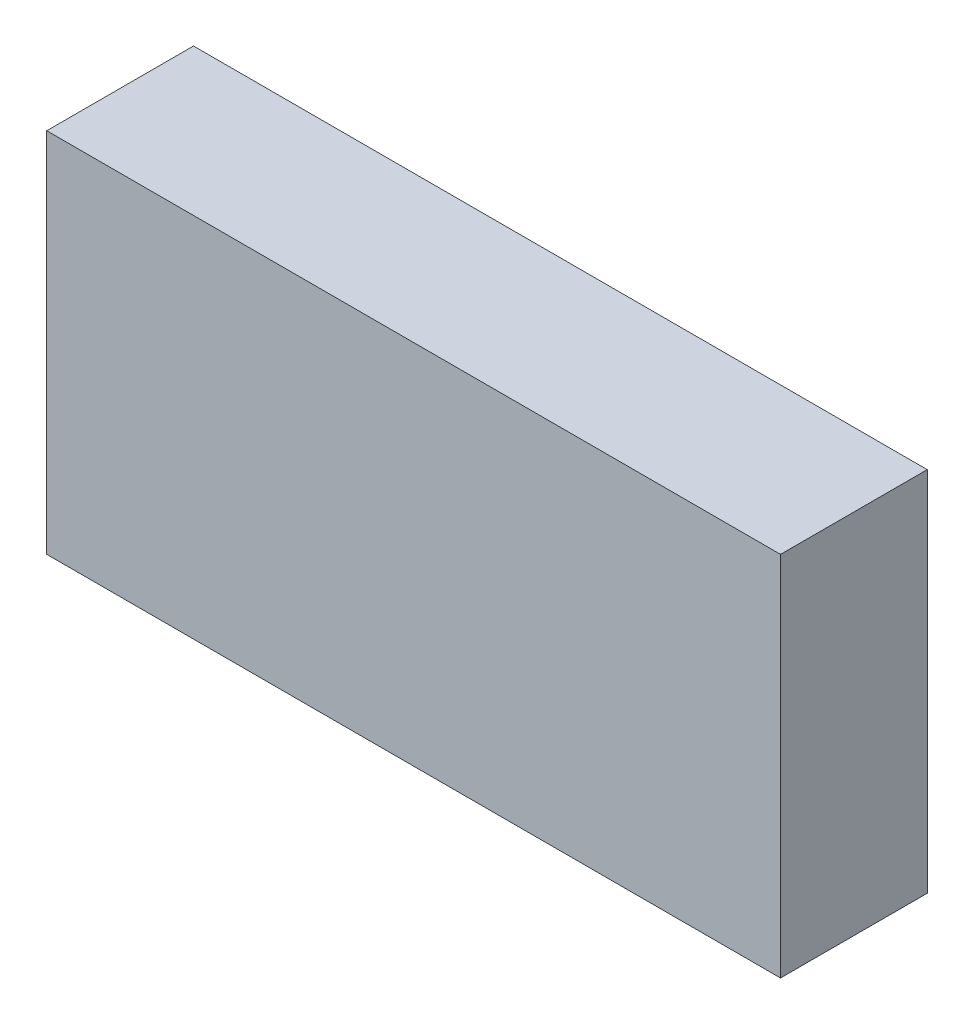
SolidWorks part; units mm, degrees
ref_plane "前视基准面" through (0, 0, 0) normal (0, 0, 1) x (1, 0, 0)
ref_plane "上视基准面" through (0, 0, 0) normal (0, 1, 0) x (1, 0, 0)
ref_plane "右视基准面" through (0, 0, 0) normal (1, 0, 0) x (0, 0, -1)
other "Configuration Table"
sketch "草图1" plane through (0, 0, 0) normal (0, 0, 1) x (1, 0, 0)
  line L1 (-25, -12.5) -> (25, -12.5)
  line L2 (-25, -12.5) -> (-25, 12.5)
  line L3 (-25, 12.5) -> (25, 12.5)
  line L4 (25, -12.5) -> (25, 12.5)
  line L5 (-25, -12.5) -> (25, 12.5) construction
  line L6 (-25, 12.5) -> (25, -12.5) construction
  point P0 (0, 0)
extrude "凸台-拉伸1" add sketch "草图1" along normal blind 10
